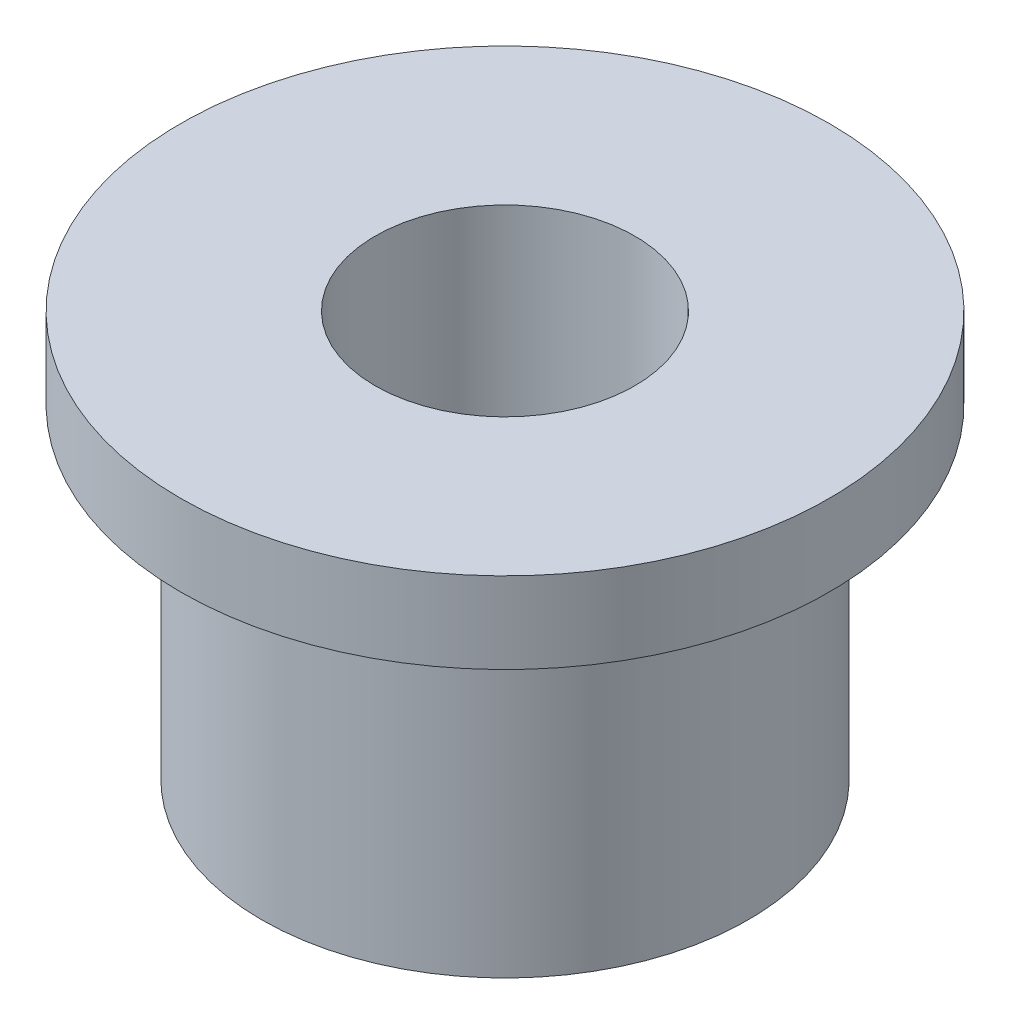
SolidWorks part; units mm, degrees
ref_plane "Plano frontal" through (0, 0, 0) normal (0, 0, 1) x (1, 0, 0)
ref_plane "Plano superior" through (0, 0, 0) normal (0, 1, 0) x (1, 0, 0)
ref_plane "Plano direito" through (0, 0, 0) normal (1, 0, 0) x (0, 0, -1)
sketch "Esboço1" plane through (0, 0, 0) normal (0, 1, 0) x (1, 0, 0)
  circle A0 centre (0, 0) radius 1.6
  circle A1 centre (0, 0) radius 3
  dimension "D1" = 3.2
  dimension "D2" = 6
extrude "Ressalto-extrusão1" add sketch "Esboço1" along normal blind 5
sketch "Esboço2" plane through (0, 5, 0) normal (0, 1, 0) x (1, 0, 0)
  circle A0 centre (0, 0) radius 3
  circle A1 centre (0, 0) radius 4
  dimension "D1" = 8
  dimension "D2" = 6
extrude "Ressalto-extrusão2" add sketch "Esboço2" against normal blind 1
